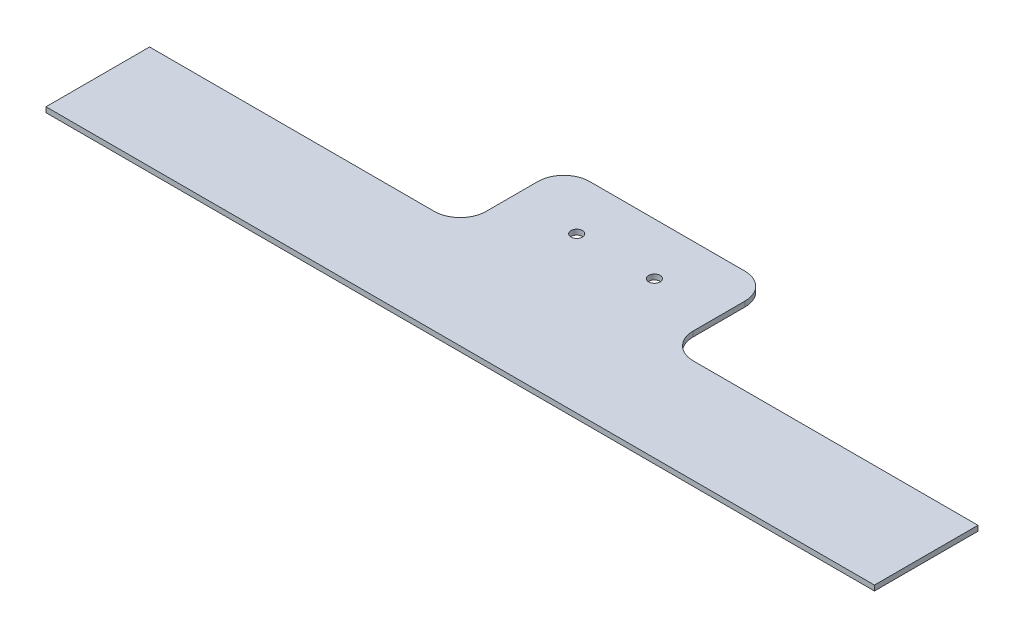
SolidWorks part; units mm, degrees
ref_plane "Front" through (0, 0, 0) normal (0, 0, 1) x (1, 0, 0)
ref_plane "Top" through (0, 0, 0) normal (0, 1, 0) x (1, 0, 0)
ref_plane "Right" through (0, 0, 0) normal (1, 0, 0) x (0, 0, -1)
sketch "Sketch1" plane through (0, 0, 0) normal (0, 1, 0) x (1, 0, 0)
  line L1 (0, 0) -> (406.4, 0)
  line L2 (0, 0) -> (0, 50.8)
  line L3 (0, 50.8) -> (406.4, 50.8)
  line L4 (406.4, 0) -> (406.4, 50.8)
  line L5 (152.4, 50.8) -> (254, 50.8)
  line L6 (152.4, 50.8) -> (152.4, 101.6)
  line L7 (152.4, 101.6) -> (254, 101.6)
  line L8 (254, 50.8) -> (254, 101.6)
  dimension "D1" = 406.4
  dimension "D2" = 50.8
  dimension "D3" = 101.6
  dimension "D4" = 152.4
  dimension "D5" = 50.8
extrude "Boss-Extrude1" add sketch "Sketch1" along normal blind 2.54 contours L1 L4 L3 L2 | L3 L8 L7 L6
sketch "Sketch2" plane through (0, 2.54, 0) normal (0, 1, 0) x (1, 0, 0)
  line L0 (254, 50.8) -> (254, 101.6) construction
  line L1 (152.4, 50.8) -> (152.4, 101.6) construction
  line L2 (152.4, 101.6) -> (254, 101.6) construction
  circle A0 centre (222.25, 76.2) radius 2.794
  circle A1 centre (184.15, 76.2) radius 2.794
  dimension "D1" = 5.588
  dimension "D2" = 5.588
  dimension "D3" = 31.75
  dimension "D4" = 31.75
  dimension "D5" = 25.4
  dimension "D6" = 25.4
extrude "Cut-Extrude1" cut sketch "Sketch2" against normal blind 2.54
fillet "Fillet1" radius 12.7 2 edges at (254, 1.27, -101.6) (152.4, 1.27, -101.6)
fillet "Fillet2" radius 12.7 2 edges at (152.4, 1.27, -50.8) (254, 1.27, -50.8)
